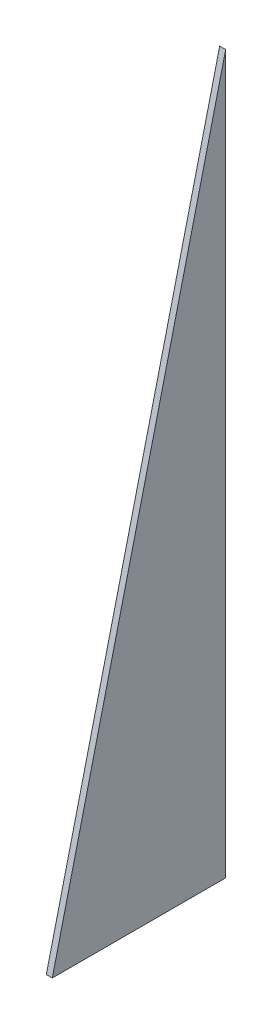
SolidWorks part; units mm, degrees
ref_plane "Alzado" through (0, 0, 0) normal (0, 0, 1) x (1, 0, 0)
ref_plane "Planta" through (0, 0, 0) normal (0, 1, 0) x (1, 0, 0)
ref_plane "Vista lateral" through (0, 0, 0) normal (1, 0, 0) x (0, 0, -1)
sketch "Croquis1" plane through (0, 0, 0) normal (1, 0, 0) x (0, 0, -1)
  line L0 (72.5, 300) -> (-72.5, -300)
  line L1 (72.5, -300) -> (-72.5, -300)
  line L2 (72.5, -300) -> (72.5, 300)
  line L3 (72.5, 300) -> (-72.5, 300)
  line L4 (-72.5, -300) -> (-72.5, 300)
  line L5 (72.5, -300) -> (-72.5, 300) construction
  line L6 (72.5, 300) -> (-72.5, -300) construction
  point P0 (0, 0)
  dimension "D1" = 600
  dimension "D2" = 145
extrude "Saliente-Extruir1" add sketch "Croquis1" along normal blind 5 contours L1 L2 L0
